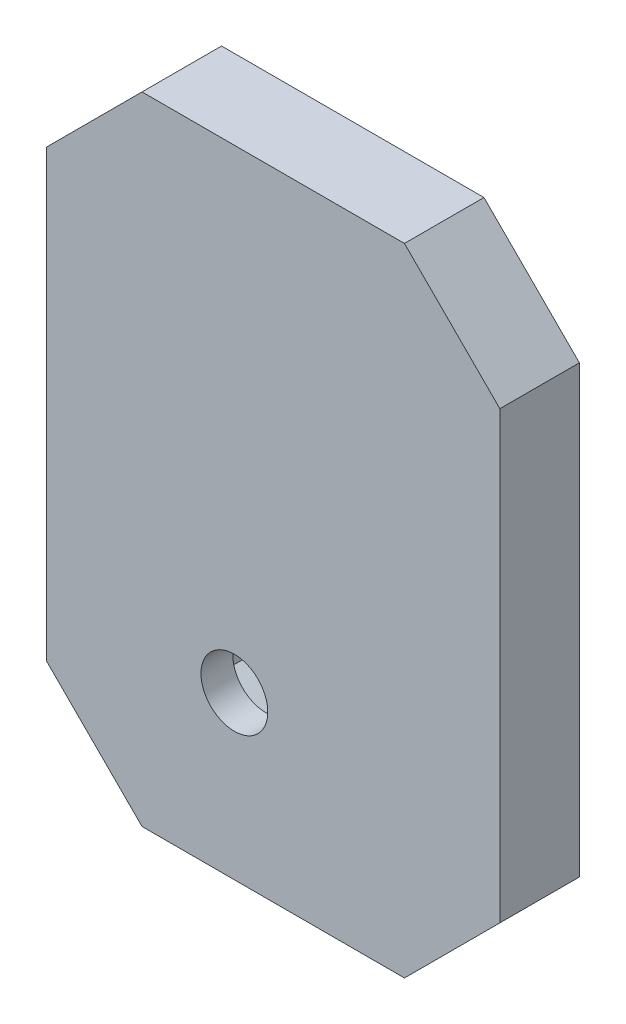
SolidWorks part; units mm, degrees
ref_plane "Front Plane" through (0, 0, 0) normal (0, 0, 1) x (1, 0, 0)
ref_plane "Top Plane" through (0, 0, 0) normal (0, 1, 0) x (1, 0, 0)
ref_plane "Right Plane" through (0, 0, 0) normal (1, 0, 0) x (0, 0, -1)
sketch "Sketch1" plane through (0, 0, 444.6201) normal (0, 0, -1) x (-1, 0, 0)
  line L1 (161.2108, -490.2989) -> (132.7108, -490.2989)
  line L2 (161.2108, -490.2989) -> (161.2108, -530.2989)
  line L3 (161.2108, -530.2989) -> (132.7108, -530.2989)
  line L4 (132.7108, -490.2989) -> (132.7108, -530.2989)
  line L9 (149.4034, -524.3277) -> (153.0534, -522.2203)
  line L10 (153.0534, -522.2203) -> (153.0534, -518.0057)
  line L11 (153.0534, -518.0057) -> (149.4034, -515.8983)
  line L12 (149.4034, -515.8983) -> (145.7534, -518.0057)
  line L13 (145.7534, -518.0057) -> (145.7534, -522.2203)
  line L14 (145.7534, -522.2203) -> (149.4034, -524.3277)
  circle A0 centre (149.4034, -520.113) radius 3.65 construction
  dimension "D1" = 40
  dimension "D2" = 28.5
  dimension "D3" = 8.1574
  dimension "D4" = 7.3
extrude "Boss-Extrude1" add sketch "Sketch1" along normal blind 5
sketch "Sketch2" plane through (0, 0, 444.6201) normal (0, 0, -1) x (-1, 0, 0)
  line L1 (132.7108, -530.2989) -> (161.2108, -530.2989)
  line L2 (132.7108, -530.2989) -> (132.7108, -490.2989)
  line L3 (132.7108, -490.2989) -> (161.2108, -490.2989)
  line L4 (161.2108, -530.2989) -> (161.2108, -490.2989)
  circle A0 centre (149.4034, -520.113) radius 2.1
  dimension "D1" = 4.2
extrude "Boss-Extrude2" add sketch "Sketch2" along normal blind 2
chamfer "Chamfer1" distance 6 angle 45 4 edges at (-161.2108, -490.2989, 442.1201) (-161.2108, -530.2989, 442.1201) (-132.7108, -530.2989, 442.1201) (-132.7108, -490.2989, 442.1201)
